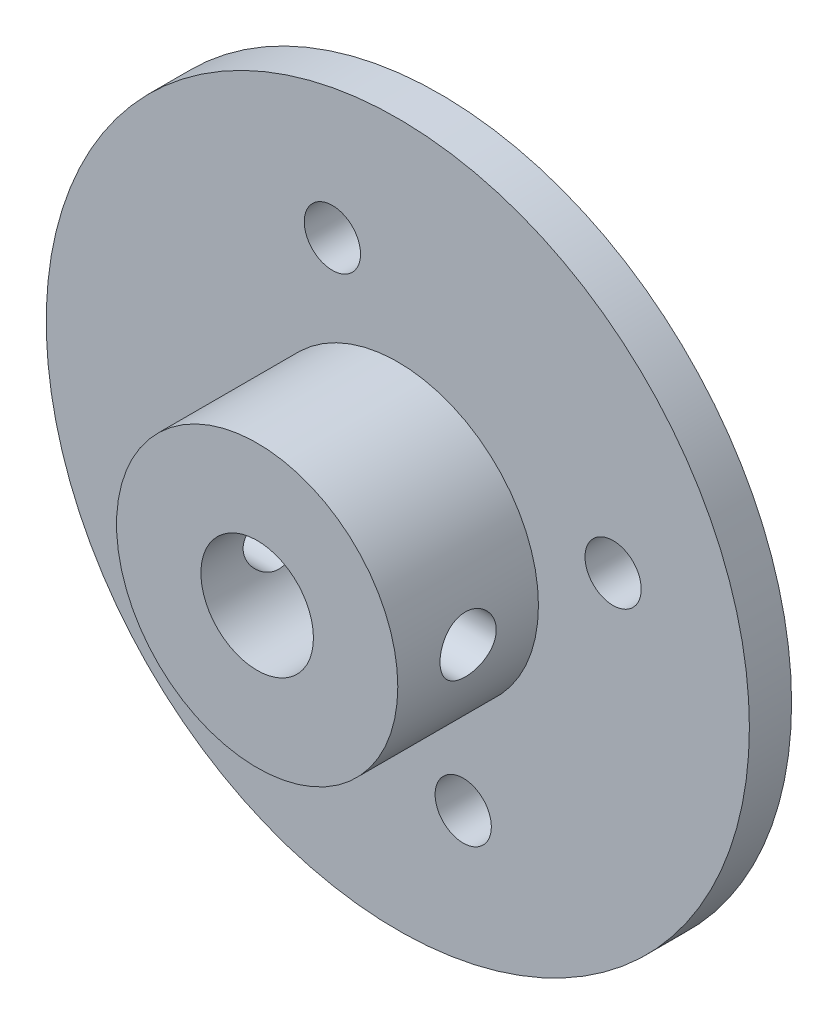
SolidWorks part; units mm, degrees
material "Bronce de aluminio"
ref_plane "Alzado" through (0, 0, 0) normal (0, 0, 1) x (1, 0, 0)
ref_plane "Planta" through (0, 0, 0) normal (0, 1, 0) x (1, 0, 0)
ref_plane "Vista lateral" through (0, 0, 0) normal (1, 0, 0) x (0, 0, -1)
sketch "Croquis1" plane through (0, 0, 0) normal (0, 0, 1) x (1, 0, 0)
  circle A0 centre (0, 0) radius 25
  dimension "D1" = 50
extrude "Saliente-Extruir1" add sketch "Croquis1" along normal blind 3
sketch "Croquis2" plane through (0, 0, 3) normal (0, 0, 1) x (1, 0, 0)
  circle A0 centre (0, 0) radius 10
  dimension "D1" = 20
extrude "Saliente-Extruir2" add sketch "Croquis2" along normal blind 10
sketch "Croquis3" plane through (0, 0, 13) normal (0, 0, 1) x (1, 0, 0)
  circle A0 centre (0, 0) radius 4
  dimension "D1" = 8
extrude "Cortar-Extruir1" cut sketch "Croquis3" against normal through all
sketch "Croquis4" plane through (0, 0, 3) normal (0, 0, 1) x (1, 0, 0)
  circle A0 centre (-4.6517, 15.3089) radius 2
  circle A1 centre (15.3089, 4.6517) radius 2
  circle A2 centre (4.6517, -15.3089) radius 2
  circle A3 centre (-15.3089, -4.6517) radius 2
  point P11 (0, 0)
  dimension "D2" = 4
  dimension "D3" = 16
  dimension "D1" = 4
extrude "Cortar-Extruir2" cut sketch "Croquis4" against normal through all
sketch "Croquis5" plane through (0, 0, 0) normal (1, 0, 0) x (0, 0, -1)
  line L0 (-13, 0) -> (-3, 0) construction
  line L1 (-13, 10) -> (-13, -10) construction
  line L2 (-3, 10) -> (-13, 10) construction
  line L3 (-13, -10) -> (-3, -10) construction
  line L4 (-3, 10) -> (-3, -10) construction
  circle A0 centre (-8, 0) radius 2
  dimension "D1" = 4
extrude "Cortar-Extruir3" cut sketch "Croquis5" against normal through all and the other way through all
